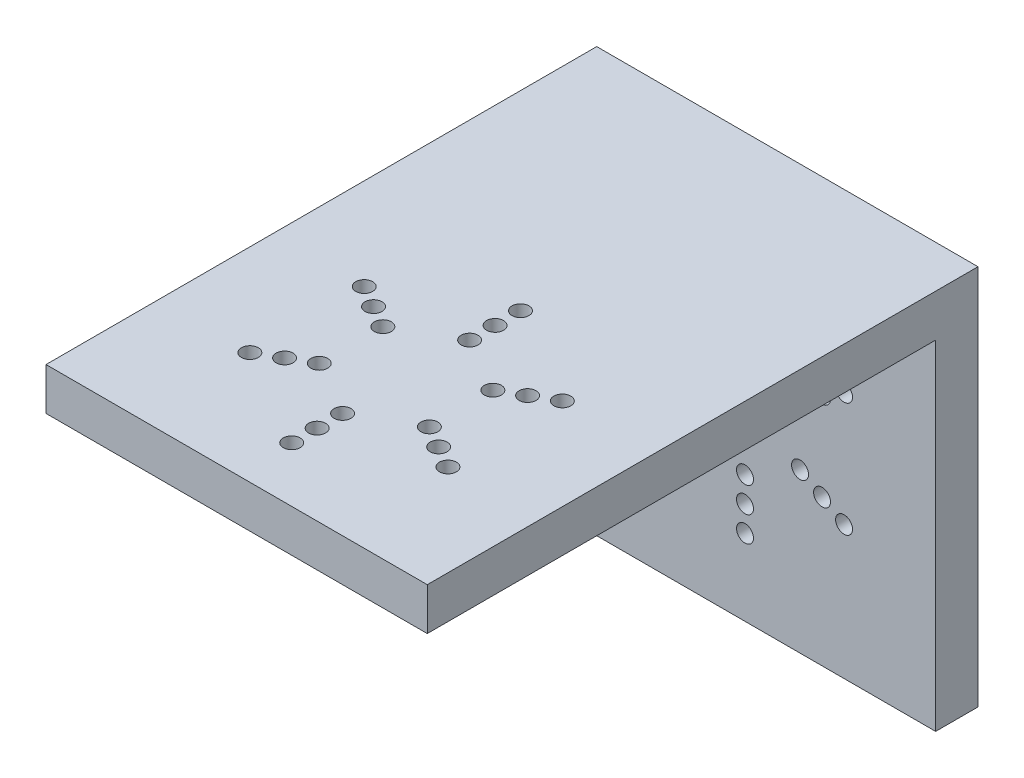
SolidWorks part; units mm, degrees
material "Polylactic Acid"
ref_plane "Front Plane" through (0, 0, 0) normal (0, 0, 1) x (1, 0, 0)
ref_plane "Top Plane" through (0, 0, 0) normal (0, 1, 0) x (1, 0, 0)
ref_plane "Right Plane" through (0, 0, 0) normal (1, 0, 0) x (0, 0, -1)
sketch "Sketch1" plane through (0, 0, 0) normal (0, 0, 1) x (1, 0, 0)
  line L0 (0, -13.5) -> (0, -10.5) construction
  line L1 (-22.5, -22.5) -> (22.5, -22.5)
  line L2 (-22.5, -22.5) -> (-22.5, 22.5)
  line L3 (-22.5, 22.5) -> (22.5, 22.5)
  line L4 (22.5, -22.5) -> (22.5, 22.5)
  line L5 (-22.5, -22.5) -> (22.5, 22.5) construction
  line L6 (-22.5, 22.5) -> (22.5, -22.5) construction
  line L7 (0, 0) -> (0, -7.5) construction
  circle A0 centre (0, -13.5) radius 1
  circle A1 centre (0, -10.5) radius 1
  circle A2 centre (0, -7.5) radius 1
  circle A3 centre (-11.6913, -6.75) radius 1
  circle A4 centre (-9.0933, -5.25) radius 1
  circle A5 centre (-6.4952, -3.75) radius 1
  circle A6 centre (-11.6913, 6.75) radius 1
  circle A7 centre (-9.0933, 5.25) radius 1
  circle A8 centre (-6.4952, 3.75) radius 1
  circle A9 centre (0, 13.5) radius 1
  circle A10 centre (0, 10.5) radius 1
  circle A11 centre (0, 7.5) radius 1
  circle A12 centre (11.6913, 6.75) radius 1
  circle A13 centre (9.0933, 5.25) radius 1
  circle A14 centre (6.4952, 3.75) radius 1
  circle A15 centre (11.6913, -6.75) radius 1
  circle A16 centre (9.0933, -5.25) radius 1
  circle A17 centre (6.4952, -3.75) radius 1
  point P0 (0, 0)
  dimension "D3" = 2
  dimension "D1" = 3
  dimension "D5" = 7.5
  dimension "D6" = 45
  dimension "D7" = 45
  dimension "D2" = 3
  dimension "D4" = 6
extrude "Boss-Extrude1" add sketch "Sketch1" along normal blind 5
sketch "Sketch2" plane through (0, 0, 5) normal (0, 0, 1) x (1, 0, 0)
  line L1 (22.5, 22.5) -> (-22.5, 22.5)
  line L2 (22.5, 22.5) -> (22.5, 17.5)
  line L3 (22.5, 17.5) -> (-22.5, 17.5)
  line L4 (-22.5, 22.5) -> (-22.5, 17.5)
  line L5 (-22.5, 22.5) -> (-22.5, -22.5) construction
  point P5 (-22.5, 17.3503)
  dimension "D1" = 5
extrude "Boss-Extrude2" add sketch "Sketch2" along normal blind 60
sketch "Sketch3" plane through (-5, 17.5, 0) normal (0, 1, 0) x (0, 0, -1)
  line L0 (-58.5, -5) -> (-55.5, -5) construction
  line L1 (-45, -5) -> (-52.5, -5) construction
  line L3 (-65, -27.5) -> (-65, 17.5) construction
  circle A18 centre (-58.5, -5) radius 1
  circle A19 centre (-55.5, -5) radius 1
  circle A20 centre (-52.5, -5) radius 1
  circle A21 centre (-51.75, 6.6913) radius 1
  circle A22 centre (-50.25, 4.0933) radius 1
  circle A23 centre (-48.75, 1.4952) radius 1
  circle A24 centre (-38.25, 6.6913) radius 1
  circle A25 centre (-39.75, 4.0933) radius 1
  circle A26 centre (-41.25, 1.4952) radius 1
  circle A27 centre (-31.5, -5) radius 1
  circle A28 centre (-34.5, -5) radius 1
  circle A29 centre (-37.5, -5) radius 1
  circle A30 centre (-38.25, -16.6913) radius 1
  circle A31 centre (-39.75, -14.0933) radius 1
  circle A32 centre (-41.25, -11.4952) radius 1
  circle A33 centre (-51.75, -16.6913) radius 1
  circle A34 centre (-50.25, -14.0933) radius 1
  circle A35 centre (-48.75, -11.4952) radius 1
  point P2 (-28.2574, 20)
  point P9 (0, 0)
  point P10 (-33.5979, -4.4778)
  point P46 (-32.1124, -5)
  dimension "D3" = 2
  dimension "D1" = 3
  dimension "D5" = 20
  dimension "D4" = 7.5
  dimension "D2" = 3
extrude "Cut-Extrude1" cut sketch "Sketch3" along normal up to surface (5 mm away) up to face at (0, 22.5, 32.5)
